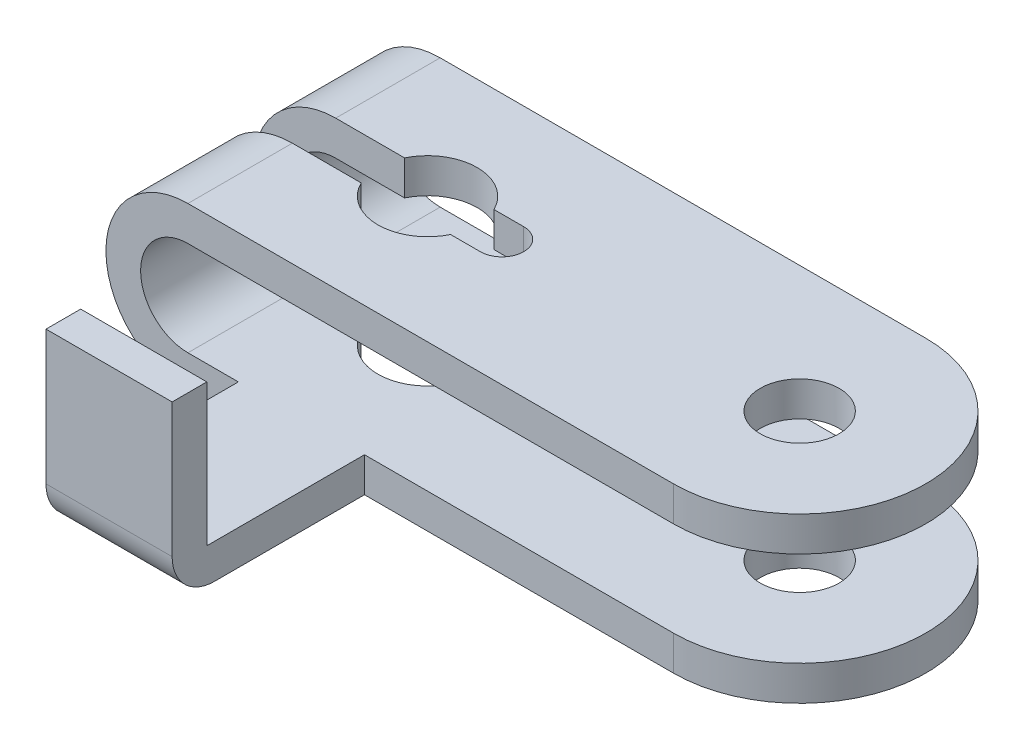
SolidWorks part; units mm, degrees
ref_plane "Alzado" through (0, 0, 0) normal (0, 0, 1) x (1, 0, 0)
ref_plane "Planta" through (0, 0, 0) normal (0, 1, 0) x (1, 0, 0)
ref_plane "Vista lateral" through (0, 0, 0) normal (1, 0, 0) x (0, 0, -1)
sketch "Croquis1" plane through (0, 0, 0) normal (0, 0, 1) x (1, 0, 0)
  line L0 (0, -8.2) -> (38.8, -8.2)
  line L1 (0, 0) -> (38.8, 0)
  line L3 (0, -10.4) -> (38.8, -10.4)
  line L5 (0, -2.2) -> (38.8, -2.2)
  line L6 (38.8, 0) -> (38.8, -2.2)
  line L7 (38.8, -8.2) -> (38.8, -10.4)
  line L8 (0, 0) -> (0, -10.4) construction
  arc A0 (0, 0) -> (0, -10.4) centre (0, -5.2) ccw
  arc A1 (0, -2.2) -> (0, -8.2) centre (0, -5.2) ccw
  arc A2 (0, 0) -> (0, -10.4) centre (0, -5.2) ccw construction
  point P13 (-5.2, -5.2)
  dimension "D2" = 10.4
  dimension "D3" = 44
  dimension "D1" = 2.2
extrude "Saliente-Extruir1" add sketch "Croquis1" along normal blind 16
sketch "Croquis2" plane through (0, 0, 0) normal (0, 1, 0) x (1, 0, 0)
  line L0 (38.8, -8) -> (-5.2, -8) construction
  line L1 (38.8, -16) -> (38.8, 0) construction
  line L2 (-5.2, 0) -> (-5.2, -16) construction
  line L3 (38.8, 0) -> (0, 0) construction
  line L4 (38.8, -16) -> (0, -16) construction
  line L5 (30.8, 0) -> (30.8, -16) construction
  line L6 (30.8, 0) -> (38.8, 0)
  line L7 (38.8, 0) -> (38.8, -16)
  line L8 (38.8, -16) -> (30.8, -16)
  line L10 (-5.2, -6.625) -> (11.925, -6.625)
  line L11 (-5.2, -6.625) -> (-5.2, -9.375)
  line L12 (-5.2, -9.375) -> (11.925, -9.375)
  line L13 (11.925, -6.625) -> (11.925, -9.375) construction
  arc A0 (30.8, 0) -> (30.8, -16) centre (30.8, -8) cw
  circle A1 centre (30.8, -8) radius 2.5
  circle A2 centre (7.2, -8) radius 3.15
  arc A3 (11.925, -6.625) -> (11.925, -9.375) centre (11.925, -8) cw
  point P23 (11.925, -8)
  point P26 (13.3, -8)
  point P27 (28.3, -8)
  line M9 (38.8, 0) -> (0, 0)
  line M10 (0, 0) -> (0, -16)
  line M11 (0, -16) -> (38.8, -16)
  line M12 (38.8, -16) -> (38.8, 0)
  dimension "D1" = 5
  dimension "D2" = 6.3
  dimension "D3" = 23.6
  dimension "D4" = 2.75
  dimension "D5" = 15
extrude "Cortar-Extruir1" cut sketch "Croquis2" against normal up to surface (10.4 mm away) contours L11 L12 L10 M10 | A2 L10 L12 M10 | L10 A2 | L12 A2 L10 | L12 A2 | A3 L10 A2 L12 | A1 | A0 L7 M9 | A0 M12 M11
sketch "Croquis5" plane through (0, 0, 16) normal (0, 0, 1) x (1, 0, 0)
  line L0 (10.0341, 0) -> (4.3659, 0) construction
  line L1 (3.2, -8.2) -> (11.2, -8.2)
  line L2 (3.2, -8.2) -> (3.2, -10.4)
  line L3 (3.2, -10.4) -> (11.2, -10.4)
  line L4 (11.2, -8.2) -> (11.2, -10.4)
  line L5 (10.0341, 0) -> (4.3659, 0)
  line L6 (7.2, 0) -> (7.2, -10.4) construction
  line L7 (0, -10.4) -> (30.8, -10.4) construction
  line L8 (30.8, -8.2) -> (0, -8.2) construction
  point P10 (7.2, -8.2)
  line M9 (0, -10.4) -> (30.8, -10.4)
  line M11 (30.8, -8.2) -> (0, -8.2)
  dimension "D1" = 8
extrude "Saliente-Extruir4" add sketch "Croquis5" along normal blind 12.2 contours L6 L1 L2 M9 | L6 L3 L4 M11
sketch "Croquis6" plane through (0, -8.2, 0) normal (0, 1, 0) x (1, 0, 0)
  line L0 (11.2, -28.2) -> (11.2, -16) construction
  line L1 (3.2, -28.2) -> (11.2, -28.2)
  line L2 (3.2, -28.2) -> (3.2, -26)
  line L3 (3.2, -26) -> (11.2, -26)
  line L4 (11.2, -28.2) -> (11.2, -26)
  dimension "D1" = 2.2
extrude "Saliente-Extruir5" add sketch "Croquis6" along normal blind 9
fillet "Redondeo2" radius 2.7 1 edges at (7.2, -10.4, 28.2)
